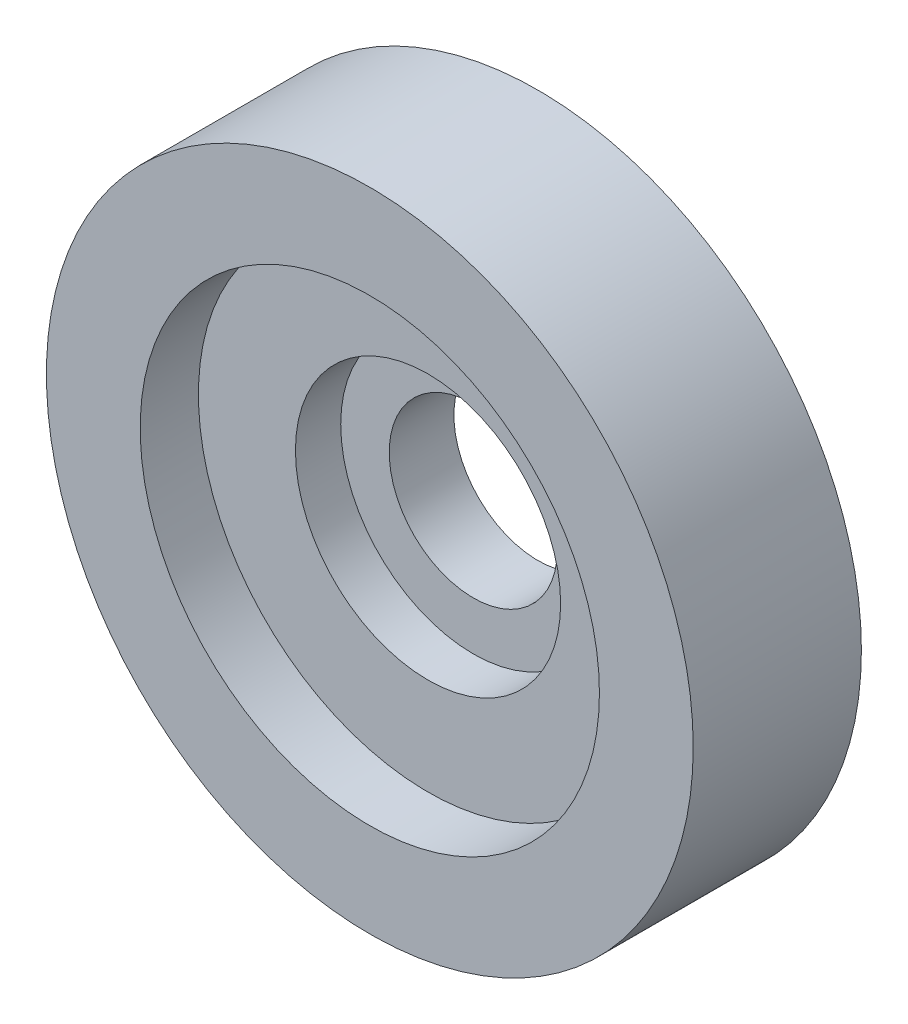
SolidWorks part; units mm, degrees
ref_plane "Alzado" through (0, 0, 0) normal (0, 0, 1) x (1, 0, 0)
ref_plane "Planta" through (0, 0, 0) normal (0, 1, 0) x (1, 0, 0)
ref_plane "Vista lateral" through (0, 0, 0) normal (1, 0, 0) x (0, 0, -1)
sketch "Croquis1" plane through (0, 0, 0) normal (0, 0, 1) x (1, 0, 0)
  circle A0 centre (0, 0) radius 25
  dimension "D1" = 50
extrude "Saliente-Extruir1" add sketch "Croquis1" against normal blind 13
sketch "Croquis2" plane through (0, 0, 0) normal (0, 0, 1) x (1, 0, 0)
  circle A0 centre (0, 0) radius 17.75
  dimension "D1" = 35.5
extrude "Cortar-Extruir1" cut sketch "Croquis2" against normal blind 4.5
sketch "Croquis3" plane through (0, 0, -4.5) normal (0, 0, 1) x (1, 0, 0)
  circle A0 centre (0, 0) radius 10.25
  dimension "D1" = 20.5
extrude "Cortar-Extruir2" cut sketch "Croquis3" against normal blind 3.5
sketch "Croquis4" plane through (0, 0, -8) normal (0, 0, 1) x (1, 0, 0)
  circle A0 centre (0, 0) radius 6.5
  dimension "D1" = 13
extrude "Cortar-Extruir3" cut sketch "Croquis4" against normal up to next
